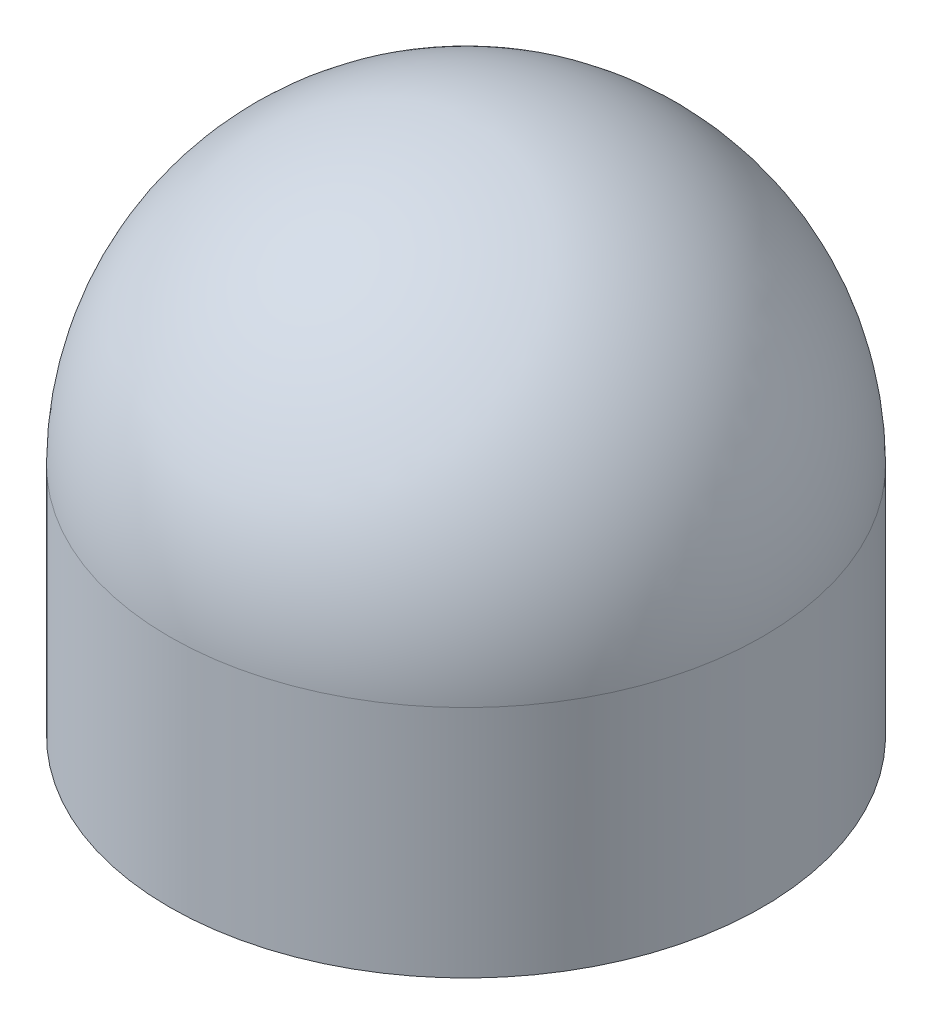
SolidWorks part; units mm, degrees
ref_plane "Front Plane" through (0, 0, 0) normal (0, 0, 1) x (1, 0, 0)
ref_plane "Top Plane" through (0, 0, 0) normal (0, 1, 0) x (1, 0, 0)
ref_plane "Right Plane" through (0, 0, 0) normal (1, 0, 0) x (0, 0, -1)
sketch "Sketch1" plane through (0, 0, 0) normal (0, 0, 1) x (1, 0, 0)
  line L0 (0, 17.272) -> (0, 7.62)
  line L5 (0, 0) -> (9.652, 0)
  line L6 (0, 0) -> (0, 7.62)
  line L8 (9.652, 0) -> (9.652, 7.62)
  arc A0 (9.652, 7.62) -> (0, 17.272) centre (0, 7.62) ccw
  dimension "D3" = 9.652
  dimension "D1" = 7.62
  dimension "D2" = 9.652
revolve "Revolve1" add sketch "Sketch1" angle 360 about L0
